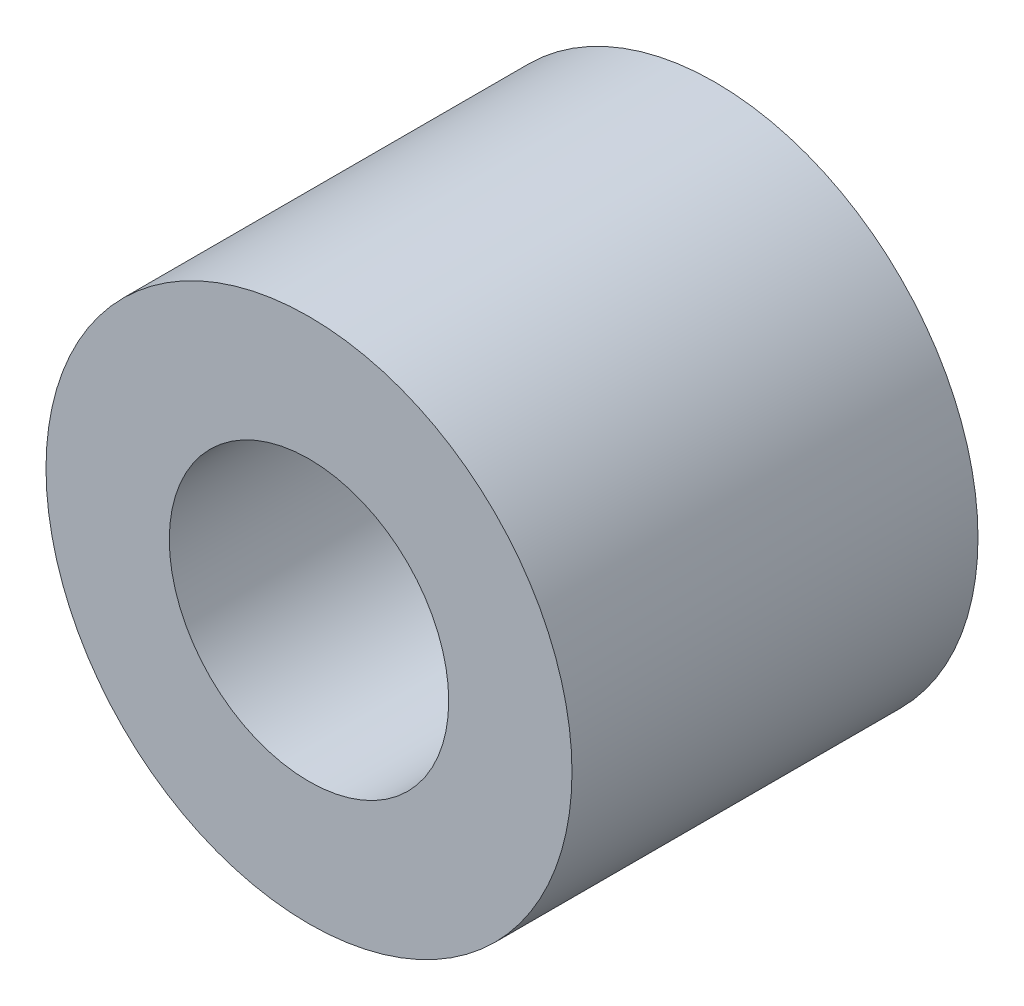
SolidWorks part; units mm, degrees
ref_plane "前视基准面" through (0, 0, 0) normal (0, 0, 1) x (1, 0, 0)
ref_plane "上视基准面" through (0, 0, 0) normal (0, 1, 0) x (1, 0, 0)
ref_plane "右视基准面" through (0, 0, 0) normal (1, 0, 0) x (0, 0, -1)
sketch "草图1" plane through (0, 0, 0) normal (0, 0, 1) x (1, 0, 0)
  circle A0 centre (0, 0) radius 4.25
  circle A1 centre (0, 0) radius 8
  dimension "D1" = 16
  dimension "D2" = 8.5
extrude "凸台-拉伸1" add sketch "草图1" along normal blind 12.35
